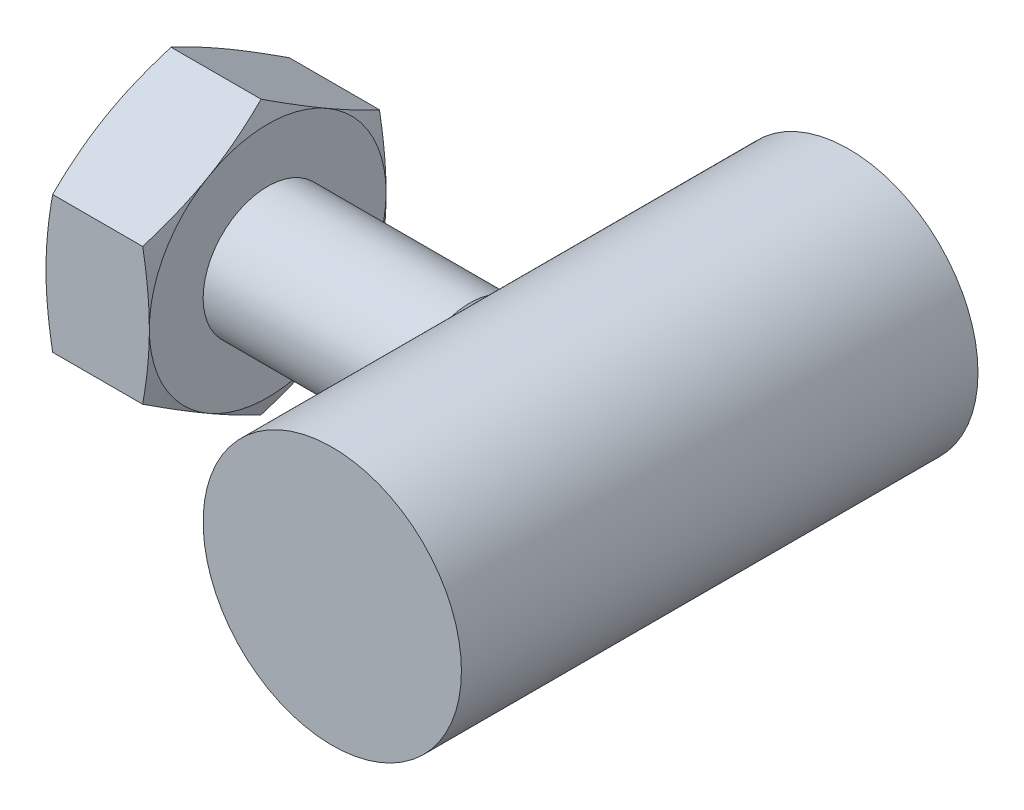
SolidWorks part; units mm, degrees
ref_plane "Front Plane" through (0, 0, 0) normal (0, 0, 1) x (1, 0, 0)
ref_plane "Top Plane" through (0, 0, 0) normal (0, 1, 0) x (1, 0, 0)
ref_plane "Right Plane" through (0, 0, 0) normal (1, 0, 0) x (0, 0, -1)
ref_plane "Plane1" through (0, 0, 0) normal (1, 0, 0) x (0, 0, -1)
sketch "Sketch1" plane through (0, 0, 0) normal (1, 0, 0) x (0, 0, -1)
  line L0 (-6, 0) -> (-6, 3)
  line L1 (-6, 3) -> (6, 3)
  line L2 (6, 3) -> (6, 0)
  line L3 (6, 0) -> (-6, 0)
  line L4 (6, 0) -> (-6, 0) construction
revolve "Revolve1" add sketch "Sketch1" angle 360 about L4
ref_plane "Plane2" through (0, 0, 0) normal (0, 0, 1) x (1, 0, 0)
sketch "Sketch2" plane through (0, 0, 0) normal (0, 0, 1) x (1, 0, 0)
  line L0 (-10, 0) -> (-10, 1.1935)
  line L1 (-10, 1.1935) -> (-9.6935, 1.5)
  line L2 (-9.6935, 1.5) -> (-2.8065, 1.5)
  line L3 (-2.8065, 1.5) -> (-2.5, 1.1935)
  line L4 (-2.5, 1.1935) -> (-2.5, 0)
  line L5 (-2.5, 0) -> (-10, 0)
  line L6 (-2.5, 0) -> (-10, 0) construction
revolve "Revolve2" add sketch "Sketch2" angle 360 about L6
cosmetic thread "Cosmetic Thread1" parameters "D1"=7.022, "D2"=2.387
ref_plane "Plane3" through (0, 0, 0) normal (0, 0, 1) x (1, 0, 0)
sketch "Sketch3" plane through (0, 0, 0) normal (0, 0, 1) x (1, 0, 0)
  line L0 (-9.9, 2.75) -> (-9.9, 1.5)
  line L1 (-9.9, 1.5) -> (-7.5, 1.5)
  line L2 (-7.5, 1.5) -> (-7.5, 2.75)
  line L3 (-7.5, 2.75) -> (-7.6548, 3.1754)
  line L4 (-7.6548, 3.1754) -> (-9.7452, 3.1754)
  line L5 (-9.7452, 3.1754) -> (-9.9, 2.75)
  line L6 (42.5, 0) -> (-57.5, 0) construction
revolve "Revolve3" add sketch "Sketch3" angle 360 about L6
ref_plane "Plane4" through (-7.5, 0, 0) normal (1, 0, 0) x (0, 0, -1)
sketch "Sketch4" plane through (-7.5, 0, 0) normal (1, 0, 0) x (0, 0, -1)
  line L0 (-5.5, -5.5) -> (5.5, -5.5)
  line L1 (5.5, -5.5) -> (5.5, 5.5)
  line L2 (5.5, 5.5) -> (-5.5, 5.5)
  line L3 (-5.5, 5.5) -> (-5.5, -5.5)
  line L4 (-2.75, -1.5877) -> (0, -3.1754)
  line L5 (0, -3.1754) -> (2.75, -1.5877)
  line L6 (2.75, -1.5877) -> (2.75, 1.5877)
  line L7 (2.75, 1.5877) -> (0, 3.1754)
  line L8 (0, 3.1754) -> (-2.75, 1.5877)
  line L9 (-2.75, 1.5877) -> (-2.75, -1.5877)
extrude "Cut-Extrude1" cut sketch "Sketch4" against normal blind 2.4
